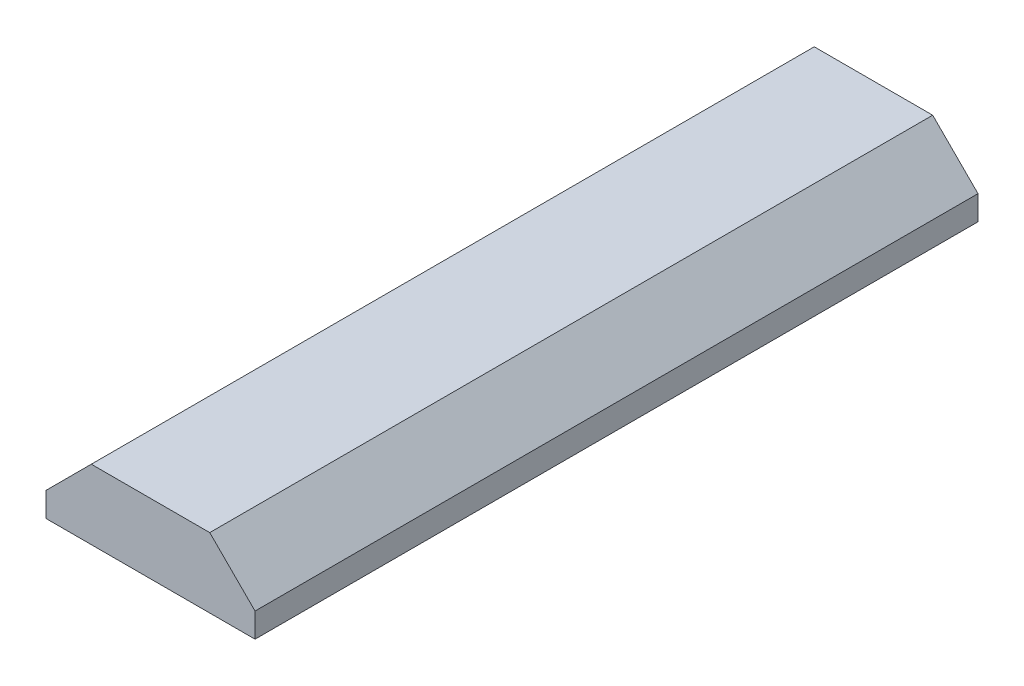
SolidWorks part; units mm, degrees
ref_plane "Ebene vorne" through (0, 0, 0) normal (0, 0, 1) x (1, 0, 0)
ref_plane "Ebene oben" through (0, 0, 0) normal (0, 1, 0) x (1, 0, 0)
ref_plane "Ebene rechts" through (0, 0, 0) normal (1, 0, 0) x (0, 0, -1)
sketch "Skizze1" plane through (0, 0, 0) normal (0, 0, 1) x (1, 0, 0)
  line L0 (0, 0) -> (0, 23680.6173) construction
  line L1 (3.4, 1.8089) -> (-3.4, 1.8089)
  line L2 (-3.4, 1.8089) -> (-6, -0.7911)
  line L3 (-6, -0.7911) -> (-6, -2.1911)
  line L4 (-6, -2.1911) -> (6, -2.1911)
  line L5 (6, -0.7911) -> (6, -2.1911)
  line L6 (3.4, 1.8089) -> (6, -0.7911)
  point P9 (0, -2.1911)
  point P11 (0, 1.8089)
  dimension "D1" = 3.4
  dimension "D2" = 6
  dimension "D3" = 4
  dimension "D4" = 135
extrude "Aufsatz-Linear austragen1" add sketch "Skizze1" along normal blind 41.5 contours L1 L2 L3 L4 L5 L6
